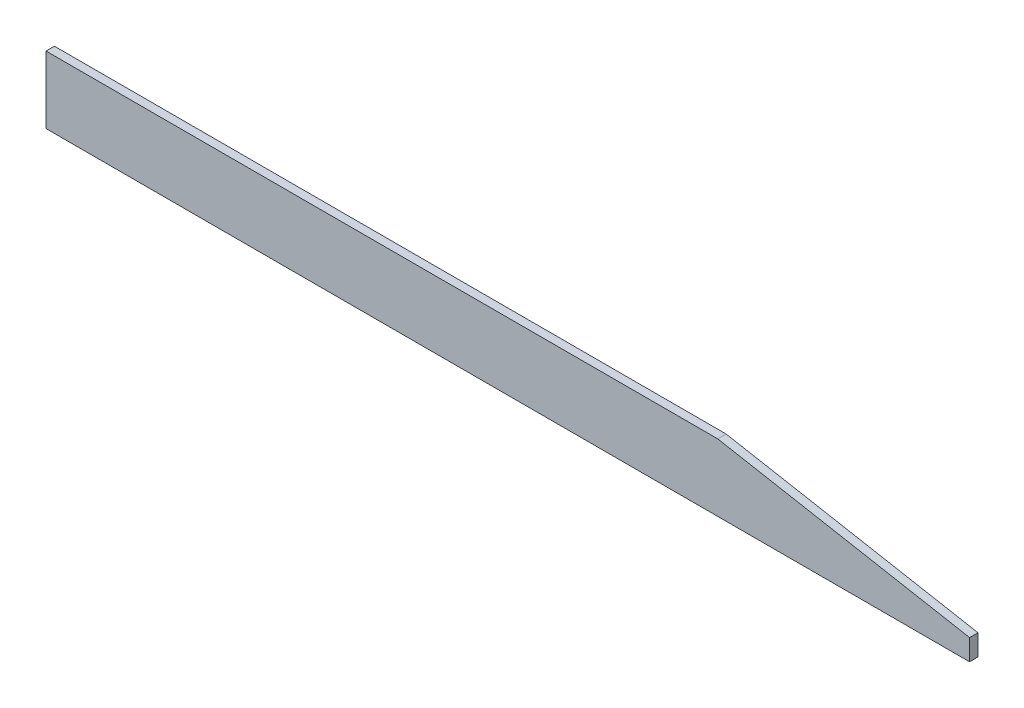
SolidWorks part; units mm, degrees
ref_plane "Face" through (0, 0, 0) normal (0, 0, 1) x (1, 0, 0)
ref_plane "Dessus" through (0, 0, 0) normal (0, 1, 0) x (1, 0, 0)
ref_plane "Droite" through (0, 0, 0) normal (1, 0, 0) x (0, 0, -1)
sketch "Esquisse1" plane through (0, 0, 0) normal (0, 0, 1) x (1, 0, 0)
  line L0 (0, 0) -> (220, 0)
  line L2 (0, 0) -> (0, 16)
  line L3 (0, 16) -> (160, 16)
  line L4 (160, 16) -> (220, 5)
  line L5 (220, 5) -> (220, 0)
  dimension "D1" = 16
  dimension "D2" = 160
  dimension "D3" = 5
  dimension "D4" = 220
extrude "Boss.-Extru.1" add sketch "Esquisse1" along normal blind 2
